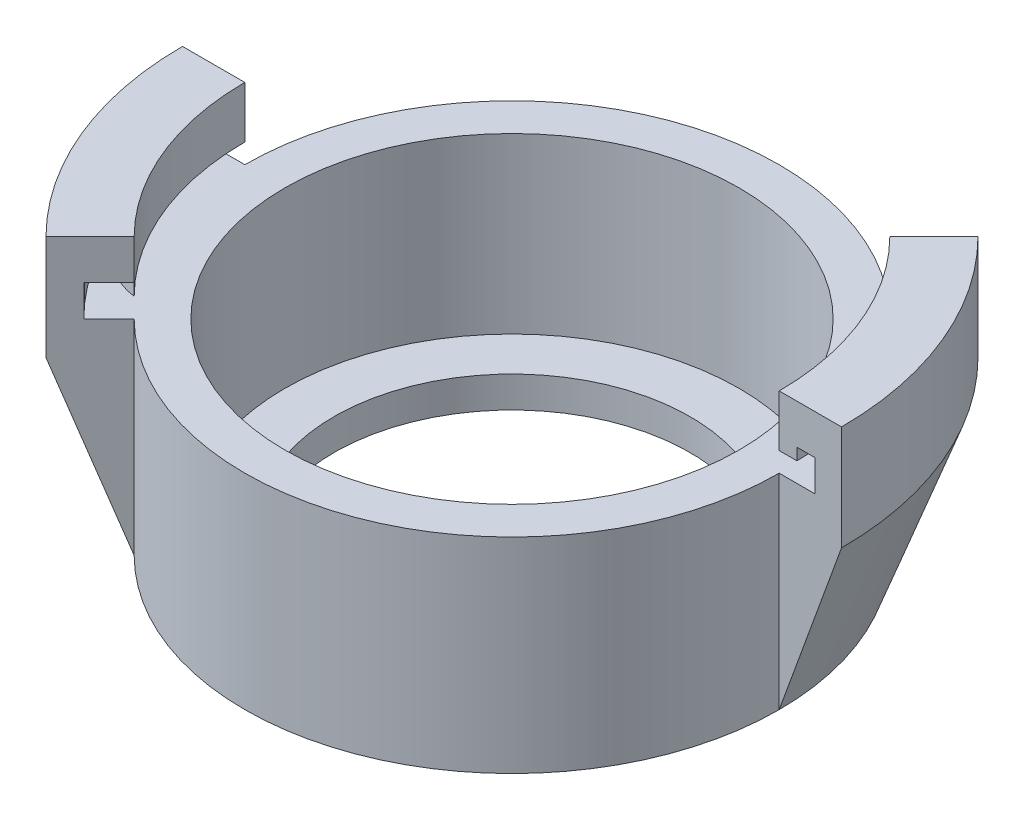
SolidWorks part; units mm, degrees
ref_plane "前视基准面" through (0, 0, 0) normal (0, 0, 1) x (1, 0, 0)
ref_plane "上视基准面" through (0, 0, 0) normal (0, 1, 0) x (1, 0, 0)
ref_plane "右视基准面" through (0, 0, 0) normal (1, 0, 0) x (0, 0, -1)
sketch "草图1" plane through (0, 0, 0) normal (0, 1, 0) x (1, 0, 0)
  circle A0 centre (0, 0) radius 30
  circle A1 centre (0, 0) radius 25.5
  dimension "D1" = 60
  dimension "D2" = 51
extrude "凸台-拉伸1" add sketch "草图1" along normal blind 23
sketch "草图2" plane through (0, 0, 0) normal (0, 1, 0) x (1, 0, 0)
  circle A0 centre (0, 0) radius 25.5
  circle A1 centre (0, 0) radius 20
extrude "凸台-拉伸2" add sketch "草图2" along normal blind 3.5
sketch "草图3" plane through (0, 0, 0) normal (0, 0, 1) x (1, 0, 0)
  line L0 (-30, 0) -> (-37, 19.23)
  line L1 (-37, 19.23) -> (-37, 31)
  line L2 (-37, 31) -> (-30, 31)
  line L3 (-30, 31) -> (-30, 25.2)
  line L4 (-30, 25.2) -> (-32, 25.2)
  line L5 (-32, 25.2) -> (-32, 26.5197)
  line L6 (-32, 26.5197) -> (-34, 26.5197)
  line L7 (-34, 26.5197) -> (-34, 23)
  line L8 (-34, 23) -> (-30, 23)
  line L9 (0, 0) -> (0, 33.1408)
  line L10 (-30, 0) -> (-30, 23)
  dimension "D1" = 19.23
  dimension "D2" = 7
  dimension "D3" = 25.2
  dimension "D4" = 31
  dimension "D5" = 5
  dimension "D6" = 3.5197
  dimension "D9" = 2
  dimension "D10" = 2
revolve "旋转1" add sketch "草图3" angle 45 about L9
ref_plane "基准面1" through (0, 0, 0) normal (0.7071, 0, 0.7071) x (0.7071, 0, -0.7071)
sketch "草图4" plane through (0, 3.5, 0) normal (0, 1, 0) x (1, 0, 0)
  line L0 (-27.7164, -11.4805) -> (27.7164, 11.4805)
  line L1 (0, 0) -> (11.4805, -27.7164)
  arc A0 (-30, 0) -> (-21.2132, -21.2132) centre (0, 0) ccw construction
  arc A1 (-21.2132, -21.2132) -> (-30, 0) centre (0, 0) ccw construction
  dimension "D1" = 90
ref_plane "基准面2" through (0, 0, 0) normal (0.9239, 0, -0.3827) x (-0.3827, 0, -0.9239)
mirror "镜向1" about plane through (0, 0, 0) normal (0.9239, 0, -0.3827) of "旋转1"
sketch "草图5" plane through (0, 25.2, 0) normal (0, -1, 0) x (1, 0, 0)
  line L0 (-26.4054, 18.0763) -> (-25.6722, 21.2132)
  line L1 (-25.6722, 21.2132) -> (-22.0631, 24.9499)
  line L2 (-22.0631, 24.9499) -> (-17.9912, 21.673)
  line L3 (-17.9912, 21.673) -> (-21.2132, 21.2132)
  arc A0 (-21.2132, 21.2132) -> (-26.4054, 18.0763) centre (-20.3591, 13.934) ccw
  arc A1 (-22.6274, 22.6274) -> (-32, 0) centre (0, 0) ccw construction
sketch "草图6" plane through (0, 0, 0) normal (1, 0, 0) x (0, 0, -1)
  line L0 (0, 25.115) -> (0, 37.4172)
  line L1 (0, 19.23) -> (0, 31) construction
extrude "切除-拉伸1" cut sketch "草图5" against normal blind 1.32
ref_plane "基准面3" through (-4.3934, 0, -10.6066) normal (0.3827, 0, 0.9239) x (0, -1, 0)
sketch "草图7" plane through (0, 25.2, 0) normal (0, -1, 0) x (1, 0, 0)
  line L0 (-27.7164, 11.4805) -> (27.7164, -11.4805) construction
  line L1 (-27.7164, 11.4805) -> (27.7164, -11.4805)
  arc A0 (-21.2132, 21.2132) -> (-30, 0) centre (0, 0) ccw construction
  arc A1 (21.2132, -21.2132) -> (30, 0) centre (0, 0) ccw construction
sketch "草图8" plane through (0, 25.2, 0) normal (0, -1, 0) x (1, 0, 0)
  line L1 (26.4078, -18.0729) -> (22.8749, -24.3452)
  line L2 (22.8749, -24.3452) -> (19.319, -22.3424)
  line L3 (19.319, -22.3424) -> (21.2132, -21.2132)
  arc A0 (21.2132, -21.2132) -> (26.4078, -18.0729) centre (20.3563, -13.9293) ccw
  arc A1 (22.6274, -22.6274) -> (32, 0) centre (0, 0) ccw construction
  dimension "D1" = 6.07
extrude "切除-拉伸3" cut sketch "草图8" against normal blind 1.32
